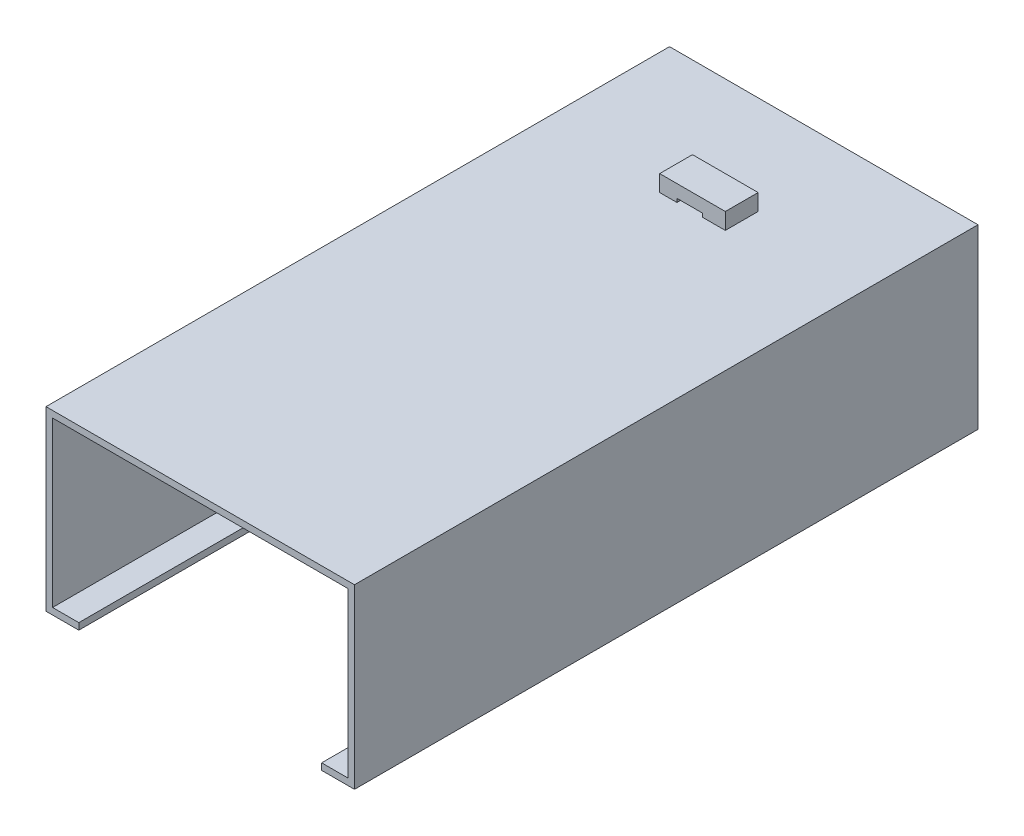
SolidWorks part; units mm, degrees
ref_plane "Front Plane" through (0, 0, 0) normal (0, 0, 1) x (1, 0, 0)
ref_plane "Top Plane" through (0, 0, 0) normal (0, 1, 0) x (1, 0, 0)
ref_plane "Right Plane" through (0, 0, 0) normal (1, 0, 0) x (0, 0, -1)
sketch "Sketch1" plane through (0, 0, 0) normal (0, 0, 1) x (1, 0, 0)
  line L0 (-5.715, 3.175) -> (-5.715, -3.175)
  line L1 (-5.969, 3.429) -> (5.969, 3.429)
  line L2 (-5.969, 3.429) -> (-5.969, -3.429)
  line L3 (-5.969, -3.429) -> (-4.699, -3.429)
  line L4 (5.969, 3.429) -> (5.969, -3.429)
  line L5 (-5.969, 3.429) -> (5.969, -3.429) construction
  line L6 (-5.969, -3.429) -> (5.969, 3.429) construction
  line L7 (-5.715, -3.175) -> (-4.699, -3.175)
  line L8 (5.715, 3.175) -> (5.715, -3.175)
  line L9 (-5.715, 3.175) -> (5.715, 3.175)
  line L10 (-5.715, -3.175) -> (-4.699, -3.175) construction
  line L11 (-4.699, -3.175) -> (-4.699, -3.429)
  line L12 (0, 3.429) -> (0, -3.429) construction
  line L13 (4.699, -3.175) -> (4.699, -3.429)
  line L14 (4.699, -3.175) -> (5.715, -3.175)
  line L15 (-5.715, -3.175) -> (5.715, -3.175) construction
  line L16 (4.699, -3.429) -> (5.969, -3.429)
  line L17 (-5.969, -3.429) -> (5.969, -3.429) construction
  point P0 (0, 0)
  point P15 (0, 0)
  dimension "D1" = 11.938
  dimension "D2" = 6.858
  dimension "D4" = 1.016
  dimension "D3" = 0.254
extrude "Boss-Extrude1" add sketch "Sketch1" along normal blind 24.13
sketch "Sketch2" plane through (0, 3.429, 0) normal (0, 1, 0) x (1, 0, 0)
  line L0 (0, 0) -> (0, -4.445) construction
  line L2 (1.27, -5.08) -> (-1.27, -5.08)
  line L3 (1.27, -5.08) -> (1.27, -3.81)
  line L4 (1.27, -3.81) -> (-1.27, -3.81)
  line L5 (-1.27, -5.08) -> (-1.27, -3.81)
  line L6 (1.27, -5.08) -> (-1.27, -3.81) construction
  line L7 (1.27, -3.81) -> (-1.27, -5.08) construction
  dimension "D1" = 4.445
  dimension "D2" = 2.54
  dimension "D3" = 1.27
extrude "Boss-Extrude2" add sketch "Sketch2" along normal blind 0.635
sketch "Sketch3" plane through (0, 0, 5.08) normal (0, 0, 1) x (1, 0, 0)
  line L0 (-1.27, 3.429) -> (-0.6033, 3.429) construction
  line L1 (-1.27, 3.429) -> (1.27, 3.429) construction
  line L2 (-0.6033, 3.429) -> (0.3815, 3.429) construction
  line L3 (0.3815, 3.429) -> (1.27, 3.429) construction
  line L4 (-0.6033, 3.429) -> (0.3815, 3.429)
  line L5 (-0.6033, 3.429) -> (-0.6033, 3.5688)
  line L6 (0.3815, 3.429) -> (0.3815, 3.5688)
  line L7 (-0.6033, 3.5688) -> (0.3815, 3.5688)
extrude "Cut-Extrude1" cut sketch "Sketch3" against normal up to next
